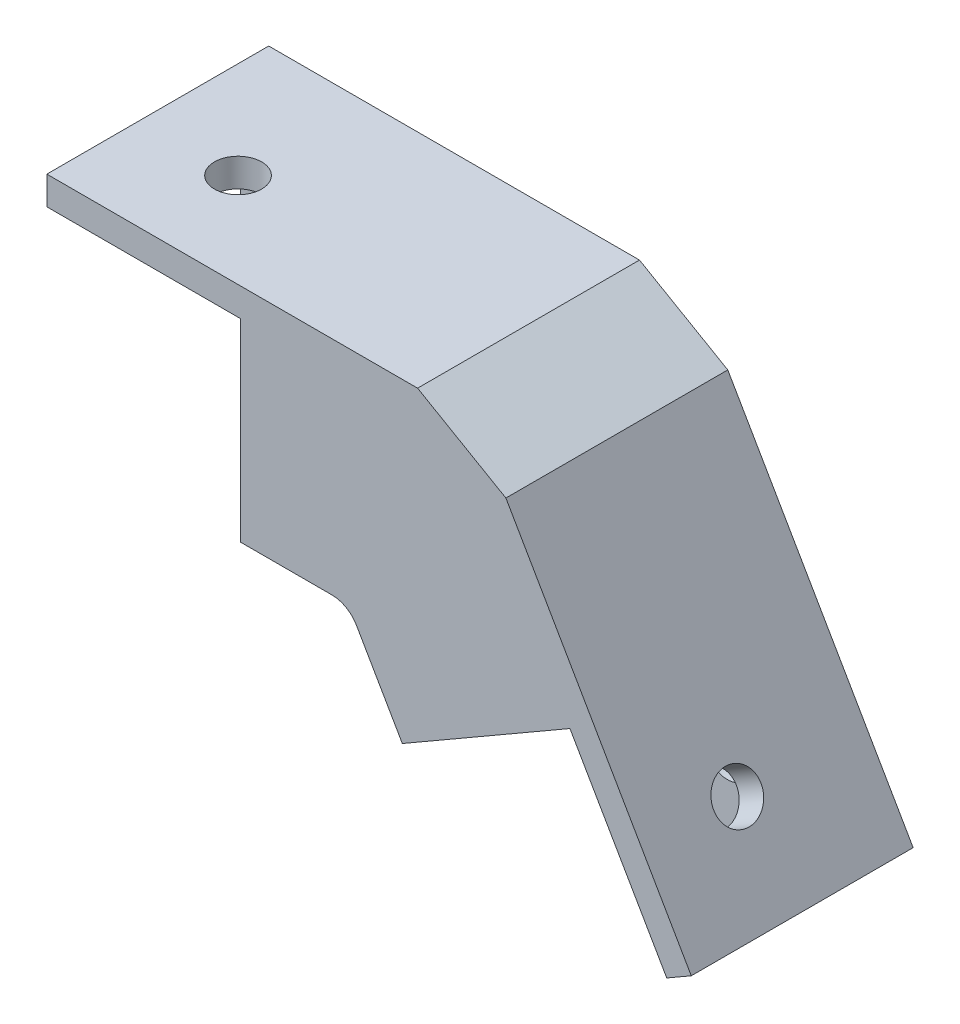
SolidWorks part; units mm, degrees
material "ABS"
ref_plane "Front Plane" through (0, 0, 0) normal (0, 0, 1) x (1, 0, 0)
ref_plane "Top Plane" through (0, 0, 0) normal (0, 1, 0) x (1, 0, 0)
ref_plane "Right Plane" through (0, 0, 0) normal (1, 0, 0) x (0, 0, -1)
sketch "Sketch1" plane through (0, 0, 0) normal (0, 0, 1) x (1, 0, 0)
  line L0 (0, 0) -> (0, 23.5)
  line L1 (0, 23.5) -> (25, 23.5)
  line L2 (25, 23.5) -> (37.5, 1.8494)
  line L3 (37.5, 1.8494) -> (17.1484, -9.9006)
  line L4 (17.1484, -9.9006) -> (11.4323, 0)
  line L5 (11.4323, 0) -> (0, 0)
  dimension "D1" = 23.5
  dimension "D2" = 120
  dimension "D3" = 25
extrude "Boss-Extrude1" add sketch "Sketch1" along normal blind 23.5
sketch "Sketch2" plane through (0, 0, 0) normal (0, 0, 1) x (1, 0, 0)
  line L0 (17.1484, -9.9006) -> (34.9019, 0.3494)
  line L1 (0, 20.5) -> (-20.5, 20.5)
  line L2 (0, 20.5) -> (0, 0)
  line L3 (0, 0) -> (-20.5, 0)
  line L4 (-20.5, 20.5) -> (-20.5, 0)
  line L5 (17.1484, -9.9006) -> (27.3984, -27.6542)
  line L6 (34.9019, 0.3494) -> (45.1519, -17.4042)
  line L7 (27.3984, -27.6542) -> (45.1519, -17.4042)
  line L8 (17.1484, -9.9006) -> (37.5, 1.8494) construction
  dimension "D1" = 20.5
  dimension "D2" = 20.5
extrude "Boss-Extrude2" add sketch "Sketch2" along normal blind 3 separate body
sketch "Sketch5" plane through (0, 0, 23.5) normal (0, 0, 1) x (1, 0, 0)
  line L0 (-20.5, 20.5) -> (-20.5, 0) construction
  line L1 (0, 20.5) -> (-20.5, 20.5)
  line L2 (0, 20.5) -> (0, 23.5)
  line L3 (0, 23.5) -> (-20.5, 23.5)
  line L4 (-20.5, 20.5) -> (-20.5, 23.5)
  line L5 (25, 23.5) -> (0, 23.5) construction
  line L6 (34.9019, 0.3494) -> (37.5, 1.8494)
  line L7 (34.9019, 0.3494) -> (45.1519, -17.4042)
  line L8 (37.5, 1.8494) -> (47.75, -15.9042)
  line L9 (45.1519, -17.4042) -> (47.75, -15.9042)
  line L10 (27.3984, -27.6542) -> (45.1519, -17.4042) construction
extrude "Boss-Extrude4" add sketch "Sketch5" against normal blind 23.5
sketch "Sketch6" plane through (0, 0, 3) normal (0, 0, -1) x (-1, 0, 0)
  line L0 (20.5, 20.5) -> (20.5, 0) construction
  line L1 (20.5, 10.25) -> (0, 10.25) construction
  line L2 (0, 0) -> (0, 20.5) construction
  line L3 (-26.0252, -4.7756) -> (-13.29, 17.2824) construction
  line L4 (-34.9019, 0.3494) -> (-17.1484, -9.9006) construction
  line L5 (-36.2752, -22.5292) -> (-26.0252, -4.7756) construction
  line L6 (-27.3984, -27.6542) -> (-45.1519, -17.4042) construction
  line L7 (20.25, 13) -> (0.25, 13)
  line L8 (20.25, 13) -> (20.25, 7.5)
  line L9 (0.25, 13) -> (0.25, 7.5)
  line L10 (20.25, 7.5) -> (0.25, 7.5)
  line L11 (20.25, 13) -> (0.25, 7.5) construction
  line L12 (0.25, 13) -> (20.25, 7.5) construction
  line L13 (-28.5317, -3.6171) -> (-38.5317, -20.9376)
  line L14 (-28.5317, -3.6171) -> (-23.7686, -6.3671)
  line L15 (-38.5317, -20.9376) -> (-33.7686, -23.6876)
  line L16 (-23.7686, -6.3671) -> (-33.7686, -23.6876)
  line L17 (-28.5317, -3.6171) -> (-33.7686, -23.6876) construction
  line L18 (-38.5317, -20.9376) -> (-23.7686, -6.3671) construction
  line L19 (-34.9019, 0.3494) -> (-17.1484, -9.9006) construction
  point P14 (10.25, 10.25)
  point P15 (-31.1502, -13.6524)
  dimension "D1" = 20
  dimension "D2" = 5.5
sketch "Sketch8" plane through (0, 20.5, 0) normal (0, -1, 0) x (1, 0, 0)
  line L0 (-20.5, 13.25) -> (0, 13.25) construction
  line L1 (-20.5, 3) -> (-20.5, 23.5) construction
  line L2 (0, 23.5) -> (0, 3) construction
  line L3 (-20.5, 23.5) -> (0, 23.5) construction
  line L4 (-0.25, 10.5) -> (-20.25, 10.5)
  line L5 (-0.25, 10.5) -> (-0.25, 16)
  line L6 (-20.25, 10.5) -> (-20.25, 16)
  line L7 (-0.25, 16) -> (-20.25, 16)
  line L8 (-0.25, 10.5) -> (-20.25, 16) construction
  line L9 (-20.25, 10.5) -> (-0.25, 16) construction
  point P9 (-10.25, 13.25)
  dimension "D1" = 10.25
  dimension "D2" = 5.5
  dimension "D3" = 20
sketch "Sketch10" plane through (26.3277, 15.2003, 0) normal (-0.866, -0.5, 0) x (0, 0, 1)
  line L0 (13.25, -37.6484) -> (13.25, -17.1484) construction
  line L1 (3, -37.6484) -> (23.5, -37.6484) construction
  line L2 (23.5, -17.1484) -> (3, -17.1484) construction
  line L3 (10.5, -17.3984) -> (10.5, -37.3984)
  line L4 (10.5, -17.3984) -> (16, -17.3984)
  line L5 (10.5, -37.3984) -> (16, -37.3984)
  line L6 (16, -17.3984) -> (16, -37.3984)
  line L7 (10.5, -17.3984) -> (16, -37.3984) construction
  line L8 (10.5, -37.3984) -> (16, -17.3984) construction
  point P7 (13.25, -27.3984)
  dimension "D1" = 5.5
  dimension "D2" = 20
sketch "Sketch12" plane through (0, 0, 23.5) normal (0, 0, 1) x (1, 0, 0)
  line L0 (23.4413, 20.8003) -> (11.4323, 0) construction
  line L1 (23.3827, -6.3013) -> (0, 7.1987)
  line L2 (23.3827, -6.3013) -> (35.1327, 14.0503)
  line L3 (0, 7.1987) -> (11.75, 27.5503)
  line L4 (35.1327, 14.0503) -> (11.75, 27.5503)
  line L5 (23.3827, -6.3013) -> (11.75, 27.5503) construction
  line L6 (0, 7.1987) -> (35.1327, 14.0503) construction
  line L7 (0, 0) -> (0, 20.5) construction
  line L8 (17.1484, -9.9006) -> (34.9019, 0.3494) construction
  point P5 (17.5663, 10.6245)
  dimension "D1" = 27
  dimension "D2" = 23.5
extrude "Boss-Extrude9" [suppressed] add sketch "Sketch12" against normal blind 45
sketch "Sketch13" [suppressed] plane through (0, 0, -21.5) normal (0, 0, -1) x (-1, 0, 0)
  line L0 (-2.5646, 5.1407) -> (-13.0646, 23.3273)
  line L1 (-2.5646, 5.1407) -> (-20.3181, -5.1093)
  line L2 (-13.0646, 23.3273) -> (-30.8181, 13.0773)
  line L3 (-20.3181, -5.1093) -> (-30.8181, 13.0773)
  line L4 (-2.5646, 5.1407) -> (-30.8181, 13.0773) construction
  line L5 (-13.0646, 23.3273) -> (-20.3181, -5.1093) construction
  line L6 (-23.4413, 20.8003) -> (-11.4323, 0) construction
  line L8 (-35.1327, 14.0503) -> (-11.75, 27.5503) construction
  line L10 (-35.1327, 14.0503) -> (-11.75, 27.5503) construction
  point P1 (-16.6913, 9.109)
  dimension "D1" = 21
  dimension "D2" = 20.5
  dimension "D3" = 3
extrude "Cut-Extrude4" [suppressed] cut sketch "Sketch13" against normal blind 40
fillet "Fillet5" radius 3 1 edges at (11.4323, 0, 11.75)
sketch "Sketch14" plane through (0, 0, 23.5) normal (0, 0, 1) x (1, 0, 0)
  line L0 (18.7654, 23.5) -> (28.1173, 18.1007)
  line L1 (18.7654, 23.5) -> (20.7654, 26.9641)
  line L2 (28.1173, 18.1007) -> (30.1173, 21.5648)
  line L3 (20.7654, 26.9641) -> (30.1173, 21.5648)
  line L4 (47.75, -15.9042) -> (25, 23.5) construction
  line L5 (25, 23.5) -> (-20.5, 23.5) construction
  line L8 (25, 23.5) -> (11.2002, -0.4019) construction
  arc A0 (12.2983, -1.5) -> (9.7002, 0) centre (9.7002, -3) ccw construction
  point P17 (23.4413, 20.8003)
  dimension "D1" = 4
  dimension "D2" = 10.7987
extrude "Cut-Extrude5" cut sketch "Sketch14" against normal through all
fillet "Fillet7" [suppressed] radius 2
sketch "Sketch16" plane through (0, 20.5, 0) normal (0, -1, 0) x (1, 0, 0)
  line L0 (-10.25, 3) -> (-10.25, 23.5) construction
  line L1 (-20.5, 3) -> (0, 3) construction
  line L2 (-20.5, 23.5) -> (0, 23.5) construction
  circle A0 centre (-10.25, 13.5) radius 2.5
  dimension "D1" = 5
  dimension "D2" = 10
extrude "Cut-Extrude7" cut sketch "Sketch16" against normal blind 40
sketch "Sketch17" plane through (26.3277, 15.2003, 0) normal (-0.866, -0.5, 0) x (0, 0, 1)
  line L0 (23.5, -27.3984) -> (3, -27.3984) construction
  line L1 (23.5, -17.1484) -> (23.5, -37.6484) construction
  line L2 (3, -17.1484) -> (3, -37.6484) construction
  circle A0 centre (13.5, -27.3984) radius 2.5
  dimension "D1" = 5
  dimension "D2" = 10
extrude "Cut-Extrude8" cut sketch "Sketch17" against normal through all
sketch "Sketch18" [suppressed] plane through (0, 0, 3) normal (0, 0, 1) x (1, 0, 0)
  line L0 (-10.25, 0) -> (-10.25, 20.5) construction
  line L1 (-20.5, 0) -> (0, 0) construction
  line L2 (-20.5, 20.5) -> (0, 20.5) construction
  line L4 (17.1484, -9.9006) -> (27.3984, -27.6542) construction
  line L5 (22.2734, -18.7774) -> (42.625, -7.0274) construction
  line L6 (47.75, -15.9042) -> (32.7942, 10) construction
  circle A0 centre (-10.25, 10) radius 2.5
  circle A1 centre (30.9337, -13.7774) radius 2.5
  dimension "D1" = 5
  dimension "D2" = 5
  dimension "D3" = 10
  dimension "D4" = 10
extrude "Cut-Extrude9" [suppressed] cut sketch "Sketch18" against normal through all
sketch "Sketch19" [suppressed] plane through (20.2655, -11.7003, 0) normal (0.866, -0.5, 0) x (0, 0, -1)
  line L0 (1.5, 16.2343) -> (21.5, 16.2343) construction
  line L2 (21.5, 6.2343) -> (21.5, 29.7343) construction
  line L4 (21.5, 6.2343) -> (0, 6.2343) construction
  line L5 (21.5, 6.2343) -> (21.5, 29.7343) construction
  circle A0 centre (11.5, 16.2343) radius 2.5
  dimension "D1" = 5
  dimension "D2" = 10
  dimension "D3" = 10
extrude "Cut-Extrude10" [suppressed] cut sketch "Sketch19" against normal through all
sketch "Sketch21" [suppressed] plane through (0, 0, 18.5) normal (0, 0, -1) x (-1, 0, 0)
  line L0 (-21.9413, 18.2023) -> (-11.4413, 0.0157) construction
  line L3 (-14.7966, 22.3273) -> (-29.0861, 14.0773) construction
  line L4 (-18.5861, -4.1093) -> (-4.2966, 4.1407) construction
  circle A0 centre (-16.6913, 9.109) radius 2.5
  dimension "D1" = 5
extrude "Cut-Extrude12" [suppressed] cut sketch "Sketch21" against normal through all
sketch "Sketch22" [suppressed] plane through (13.3671, 23.1526, 0) normal (-0.5, -0.866, 0) x (0.866, -0.5, 0)
  line L0 (9.9006, -21.5) -> (9.9006, 0) construction
  line L1 (1.6506, -21.5) -> (18.1506, -21.5) construction
  line L2 (8.4006, 0) -> (11.4006, 0) construction
  circle A0 centre (9.9006, -11.5) radius 2.5
  dimension "D1" = 5
  dimension "D2" = 10
extrude "Cut-Extrude13" [suppressed] cut sketch "Sketch22" against normal through all
sketch "Sketch23" plane through (0, 0, 3) normal (0, 0, 1) x (1, 0, 0)
  line L0 (-20.5, 20.5) -> (-20.5, 0) construction
  line L1 (-20.5, 0) -> (0, 0) construction
  line L2 (17.1484, -9.9006) -> (27.3984, -27.6542) construction
  line L3 (27.3984, -27.6542) -> (45.1519, -17.4042) construction
  circle A0 centre (-10.5, 10) radius 2.5
  circle A1 centre (31.0587, -13.9939) radius 2.5
  dimension "D1" = 10
  dimension "D2" = 10
  dimension "D3" = 10
  dimension "D5" = 5
  dimension "D4" = 10
extrude "Cut-Extrude14" cut sketch "Sketch23" against normal through all
equation "\"D2@Sketch18\"=\"D1@Sketch18\""
equation "\"D4@Sketch18\"=\"D3@Sketch18\""
